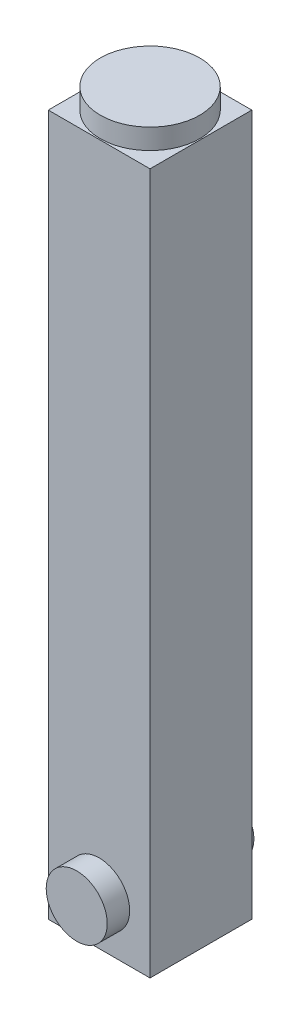
SolidWorks part; units mm, degrees
ref_plane "Alzado" through (0, 0, 0) normal (0, 0, 1) x (1, 0, 0)
ref_plane "Planta" through (0, 0, 0) normal (0, 1, 0) x (1, 0, 0)
ref_plane "Vista lateral" through (0, 0, 0) normal (1, 0, 0) x (0, 0, -1)
sketch "Croquis2" plane through (0, 0, 0) normal (0, 0, 1) x (1, 0, 0)
  line L1 (-31.75, -225) -> (31.75, -225)
  line L2 (-31.75, -225) -> (-31.75, 225)
  line L3 (-31.75, 225) -> (31.75, 225)
  line L4 (31.75, -225) -> (31.75, 225)
  line L5 (-31.75, -225) -> (31.75, 225) construction
  line L6 (-31.75, 225) -> (31.75, -225) construction
  point P0 (0, 0)
  dimension "D1" = 63.5
  dimension "D2" = 450
extrude "Saliente-Extruir1" add sketch "Croquis2" along normal blind 63.5
sketch "Croquis3" plane through (0, 0, 63.5) normal (0, 0, 1) x (1, 0, 0)
  line L0 (0, -225) -> (0, -195) construction
  line L1 (-31.75, -225) -> (31.75, -225) construction
  circle A0 centre (0, -195) radius 19.05
  dimension "D2" = 38.1
  dimension "D1" = 30
extrude "Saliente-Extruir2" add sketch "Croquis3" along normal blind 14
sketch "Croquis4" plane through (0, 0, 0) normal (0, 0, -1) x (-1, 0, 0)
  circle A0 centre (0, -195) radius 19.05
extrude "Saliente-Extruir3" add sketch "Croquis4" along normal blind 14
sketch "Croquis5" plane through (0, 225, 0) normal (0, 1, 0) x (1, 0, 0)
  line L1 (-31.75, 0) -> (31.75, 0)
  line L2 (-31.75, 0) -> (-31.75, -63.5)
  line L3 (-31.75, -63.5) -> (31.75, -63.5)
  line L4 (31.75, 0) -> (31.75, -63.5)
  line L5 (-31.75, 0) -> (31.75, -63.5) construction
  line L6 (-31.75, -63.5) -> (31.75, 0) construction
  circle A0 centre (0, -31.75) radius 31
  dimension "D1" = 62
extrude "Cortar-Extruir1" cut sketch "Croquis5" against normal blind 12.7
